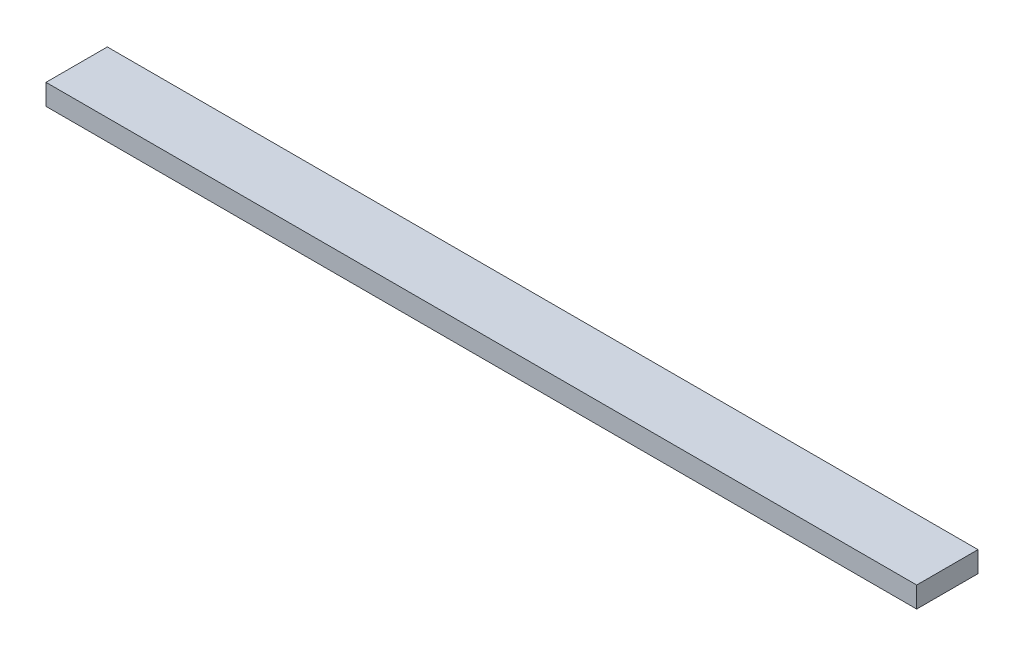
SolidWorks part; units mm, degrees
ref_plane "Front Plane" through (0, 0, 0) normal (0, 0, 1) x (1, 0, 0)
ref_plane "Top Plane" through (0, 0, 0) normal (0, 1, 0) x (1, 0, 0)
ref_plane "Right Plane" through (0, 0, 0) normal (1, 0, 0) x (0, 0, -1)
sketch "Sketch1" plane through (0, 0, 0) normal (0, 0, 1) x (1, 0, 0)
  line L1 (-35.5, 0.85) -> (35.5, 0.85)
  line L2 (-35.5, 0.85) -> (-35.5, -0.85)
  line L3 (-35.5, -0.85) -> (35.5, -0.85)
  line L4 (35.5, 0.85) -> (35.5, -0.85)
  line L5 (-35.5, 0.85) -> (35.5, -0.85) construction
  line L6 (-35.5, -0.85) -> (35.5, 0.85) construction
  point P0 (0, 0)
  dimension "D1" = 71
  dimension "D2" = 1.7
extrude "Boss-Extrude1" add sketch "Sketch1" along normal blind 5
